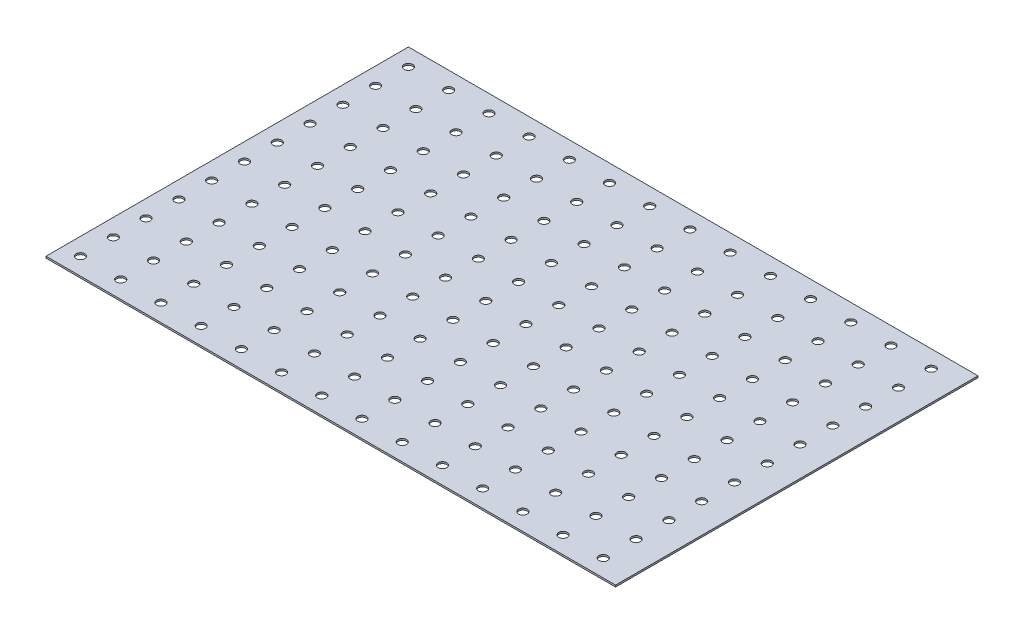
SolidWorks part; units mm, degrees
ref_plane "Front Plane" through (0, 0, 0) normal (0, 0, 1) x (1, 0, 0)
ref_plane "Top Plane" through (0, 0, 0) normal (0, 1, 0) x (1, 0, 0)
ref_plane "Right Plane" through (0, 0, 0) normal (1, 0, 0) x (0, 0, -1)
sketch "Sketch1" plane through (0, 0, 0) normal (0, 1, 0) x (1, 0, 0)
  line L1 (-208.3594, 98.8477) -> (121.6406, 98.8477)
  line L2 (-208.3594, 98.8477) -> (-208.3594, -111.1523)
  line L3 (-208.3594, -111.1523) -> (121.6406, -111.1523)
  line L4 (121.6406, 98.8477) -> (121.6406, -111.1523)
  circle A0 centre (-198.3594, 88.8477) radius 2.5
  circle A1 centre (-175.0594, 88.8477) radius 2.5
  circle A2 centre (-151.7594, 88.8477) radius 2.5
  circle A3 centre (-128.4594, 88.8477) radius 2.5
  circle A4 centre (-105.1594, 88.8477) radius 2.5
  circle A5 centre (-81.8594, 88.8477) radius 2.5
  circle A6 centre (-58.5594, 88.8477) radius 2.5
  circle A7 centre (-35.2594, 88.8477) radius 2.5
  circle A8 centre (-11.9594, 88.8477) radius 2.5
  circle A9 centre (11.3406, 88.8477) radius 2.5
  circle A10 centre (34.6406, 88.8477) radius 2.5
  circle A11 centre (57.9406, 88.8477) radius 2.5
  circle A12 centre (81.2406, 88.8477) radius 2.5
  circle A13 centre (104.5406, 88.8477) radius 2.5
  circle A15 centre (-175.0594, 69.8477) radius 2.5
  circle A16 centre (-151.7594, 69.8477) radius 2.5
  circle A17 centre (-128.4594, 69.8477) radius 2.5
  circle A18 centre (-105.1594, 69.8477) radius 2.5
  circle A19 centre (-81.8594, 69.8477) radius 2.5
  circle A20 centre (-58.5594, 69.8477) radius 2.5
  circle A21 centre (-35.2594, 69.8477) radius 2.5
  circle A22 centre (-11.9594, 69.8477) radius 2.5
  circle A23 centre (11.3406, 69.8477) radius 2.5
  circle A24 centre (34.6406, 69.8477) radius 2.5
  circle A25 centre (57.9406, 69.8477) radius 2.5
  circle A26 centre (81.2406, 69.8477) radius 2.5
  circle A27 centre (104.5406, 69.8477) radius 2.5
  circle A29 centre (-175.0594, 50.8477) radius 2.5
  circle A30 centre (-151.7594, 50.8477) radius 2.5
  circle A31 centre (-128.4594, 50.8477) radius 2.5
  circle A32 centre (-105.1594, 50.8477) radius 2.5
  circle A33 centre (-81.8594, 50.8477) radius 2.5
  circle A34 centre (-58.5594, 50.8477) radius 2.5
  circle A35 centre (-35.2594, 50.8477) radius 2.5
  circle A36 centre (-11.9594, 50.8477) radius 2.5
  circle A37 centre (11.3406, 50.8477) radius 2.5
  circle A38 centre (34.6406, 50.8477) radius 2.5
  circle A39 centre (57.9406, 50.8477) radius 2.5
  circle A40 centre (81.2406, 50.8477) radius 2.5
  circle A41 centre (104.5406, 50.8477) radius 2.5
  circle A43 centre (-175.0594, 31.8477) radius 2.5
  circle A44 centre (-151.7594, 31.8477) radius 2.5
  circle A45 centre (-128.4594, 31.8477) radius 2.5
  circle A46 centre (-105.1594, 31.8477) radius 2.5
  circle A47 centre (-81.8594, 31.8477) radius 2.5
  circle A48 centre (-58.5594, 31.8477) radius 2.5
  circle A49 centre (-35.2594, 31.8477) radius 2.5
  circle A50 centre (-11.9594, 31.8477) radius 2.5
  circle A51 centre (11.3406, 31.8477) radius 2.5
  circle A52 centre (34.6406, 31.8477) radius 2.5
  circle A53 centre (57.9406, 31.8477) radius 2.5
  circle A54 centre (81.2406, 31.8477) radius 2.5
  circle A55 centre (104.5406, 31.8477) radius 2.5
  circle A57 centre (-175.0594, 12.8477) radius 2.5
  circle A58 centre (-151.7594, 12.8477) radius 2.5
  circle A59 centre (-128.4594, 12.8477) radius 2.5
  circle A60 centre (-105.1594, 12.8477) radius 2.5
  circle A61 centre (-81.8594, 12.8477) radius 2.5
  circle A62 centre (-58.5594, 12.8477) radius 2.5
  circle A63 centre (-35.2594, 12.8477) radius 2.5
  circle A64 centre (-11.9594, 12.8477) radius 2.5
  circle A65 centre (11.3406, 12.8477) radius 2.5
  circle A66 centre (34.6406, 12.8477) radius 2.5
  circle A67 centre (57.9406, 12.8477) radius 2.5
  circle A68 centre (81.2406, 12.8477) radius 2.5
  circle A69 centre (104.5406, 12.8477) radius 2.5
  circle A71 centre (-175.0594, -6.1523) radius 2.5
  circle A72 centre (-151.7594, -6.1523) radius 2.5
  circle A73 centre (-128.4594, -6.1523) radius 2.5
  circle A74 centre (-105.1594, -6.1523) radius 2.5
  circle A75 centre (-81.8594, -6.1523) radius 2.5
  circle A76 centre (-58.5594, -6.1523) radius 2.5
  circle A77 centre (-35.2594, -6.1523) radius 2.5
  circle A78 centre (-11.9594, -6.1523) radius 2.5
  circle A79 centre (11.3406, -6.1523) radius 2.5
  circle A80 centre (34.6406, -6.1523) radius 2.5
  circle A81 centre (57.9406, -6.1523) radius 2.5
  circle A82 centre (81.2406, -6.1523) radius 2.5
  circle A83 centre (104.5406, -6.1523) radius 2.5
  circle A85 centre (-175.0594, -25.1523) radius 2.5
  circle A86 centre (-151.7594, -25.1523) radius 2.5
  circle A87 centre (-128.4594, -25.1523) radius 2.5
  circle A88 centre (-105.1594, -25.1523) radius 2.5
  circle A89 centre (-81.8594, -25.1523) radius 2.5
  circle A90 centre (-58.5594, -25.1523) radius 2.5
  circle A91 centre (-35.2594, -25.1523) radius 2.5
  circle A92 centre (-11.9594, -25.1523) radius 2.5
  circle A93 centre (11.3406, -25.1523) radius 2.5
  circle A94 centre (34.6406, -25.1523) radius 2.5
  circle A95 centre (57.9406, -25.1523) radius 2.5
  circle A96 centre (81.2406, -25.1523) radius 2.5
  circle A97 centre (104.5406, -25.1523) radius 2.5
  circle A99 centre (-175.0594, -44.1523) radius 2.5
  circle A100 centre (-151.7594, -44.1523) radius 2.5
  circle A101 centre (-128.4594, -44.1523) radius 2.5
  circle A102 centre (-105.1594, -44.1523) radius 2.5
  circle A103 centre (-81.8594, -44.1523) radius 2.5
  circle A104 centre (-58.5594, -44.1523) radius 2.5
  circle A105 centre (-35.2594, -44.1523) radius 2.5
  circle A106 centre (-11.9594, -44.1523) radius 2.5
  circle A107 centre (11.3406, -44.1523) radius 2.5
  circle A108 centre (34.6406, -44.1523) radius 2.5
  circle A109 centre (57.9406, -44.1523) radius 2.5
  circle A110 centre (81.2406, -44.1523) radius 2.5
  circle A111 centre (104.5406, -44.1523) radius 2.5
  circle A113 centre (-175.0594, -63.1523) radius 2.5
  circle A114 centre (-151.7594, -63.1523) radius 2.5
  circle A115 centre (-128.4594, -63.1523) radius 2.5
  circle A116 centre (-105.1594, -63.1523) radius 2.5
  circle A117 centre (-81.8594, -63.1523) radius 2.5
  circle A118 centre (-58.5594, -63.1523) radius 2.5
  circle A119 centre (-35.2594, -63.1523) radius 2.5
  circle A120 centre (-11.9594, -63.1523) radius 2.5
  circle A121 centre (11.3406, -63.1523) radius 2.5
  circle A122 centre (34.6406, -63.1523) radius 2.5
  circle A123 centre (57.9406, -63.1523) radius 2.5
  circle A124 centre (81.2406, -63.1523) radius 2.5
  circle A125 centre (104.5406, -63.1523) radius 2.5
  circle A127 centre (-175.0594, -82.1523) radius 2.5
  circle A128 centre (-151.7594, -82.1523) radius 2.5
  circle A129 centre (-128.4594, -82.1523) radius 2.5
  circle A130 centre (-105.1594, -82.1523) radius 2.5
  circle A131 centre (-81.8594, -82.1523) radius 2.5
  circle A132 centre (-58.5594, -82.1523) radius 2.5
  circle A133 centre (-35.2594, -82.1523) radius 2.5
  circle A134 centre (-11.9594, -82.1523) radius 2.5
  circle A135 centre (11.3406, -82.1523) radius 2.5
  circle A136 centre (34.6406, -82.1523) radius 2.5
  circle A137 centre (57.9406, -82.1523) radius 2.5
  circle A138 centre (81.2406, -82.1523) radius 2.5
  circle A139 centre (104.5406, -82.1523) radius 2.5
  circle A141 centre (-175.0594, -101.1523) radius 2.5
  circle A142 centre (-151.7594, -101.1523) radius 2.5
  circle A143 centre (-128.4594, -101.1523) radius 2.5
  circle A144 centre (-105.1594, -101.1523) radius 2.5
  circle A145 centre (-81.8594, -101.1523) radius 2.5
  circle A146 centre (-58.5594, -101.1523) radius 2.5
  circle A147 centre (-35.2594, -101.1523) radius 2.5
  circle A148 centre (-11.9594, -101.1523) radius 2.5
  circle A149 centre (11.3406, -101.1523) radius 2.5
  circle A150 centre (34.6406, -101.1523) radius 2.5
  circle A151 centre (57.9406, -101.1523) radius 2.5
  circle A152 centre (81.2406, -101.1523) radius 2.5
  circle A153 centre (104.5406, -101.1523) radius 2.5
  circle A155 centre (-198.3594, 69.8477) radius 2.5
  circle A156 centre (-198.3594, 50.8477) radius 2.5
  circle A157 centre (-198.3594, 31.8477) radius 2.5
  circle A158 centre (-198.3594, 12.8477) radius 2.5
  circle A159 centre (-198.3594, -6.1523) radius 2.5
  circle A160 centre (-198.3594, -25.1523) radius 2.5
  circle A161 centre (-198.3594, -44.1523) radius 2.5
  circle A162 centre (-198.3594, -63.1523) radius 2.5
  circle A163 centre (-198.3594, -82.1523) radius 2.5
  circle A164 centre (-198.3594, -101.1523) radius 2.5
  circle A165 centre (127.8406, 88.8477) radius 2.5 [skipped]
  circle A166 centre (127.8406, 69.8477) radius 2.5 [skipped]
  circle A167 centre (127.8406, -101.1523) radius 2.5 [skipped]
  circle A168 centre (127.8406, -63.1523) radius 2.5 [skipped]
  circle A169 centre (127.8406, -82.1523) radius 2.5 [skipped]
  circle A170 centre (127.8406, -44.1523) radius 2.5 [skipped]
  circle A171 centre (127.8406, -25.1523) radius 2.5 [skipped]
  circle A172 centre (127.8406, 12.8477) radius 2.5 [skipped]
  circle A173 centre (127.8406, 31.8477) radius 2.5 [skipped]
  circle A174 centre (127.8406, 50.8477) radius 2.5 [skipped]
  circle A175 centre (127.8406, -6.1523) radius 2.5 [skipped]
  dimension "D3" = 5
  dimension "D1" = 210
  dimension "D2" = 330
  dimension "D4" = 10
  dimension "D5" = 10
  dimension "D6" = 15
  dimension "D7" = 11
extrude "Boss-Extrude1" add sketch "Sketch1" along normal blind 1
